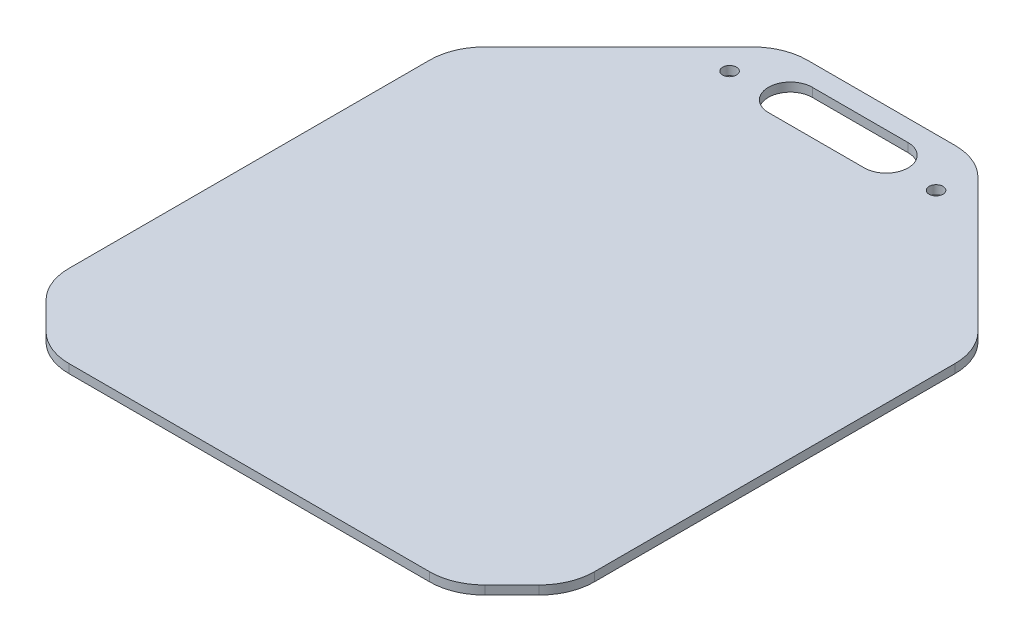
SolidWorks part; units mm, degrees
ref_plane "Front Plane" through (0, 0, 0) normal (0, 0, 1) x (1, 0, 0)
ref_plane "Top Plane" through (0, 0, 0) normal (0, 1, 0) x (1, 0, 0)
ref_plane "Right Plane" through (0, 0, 0) normal (1, 0, 0) x (0, 0, -1)
sketch "Sketch1" plane through (0, 0, 0) normal (0, 1, 0) x (1, 0, 0)
  line L0 (0, 0) -> (294, 0)
  line L1 (294, 0) -> (336.996, 43.004)
  line L2 (336.996, 43.004) -> (336.996, 337.004)
  line L3 (336.996, 337.004) -> (217, 457)
  line L4 (217, 457) -> (77, 457)
  line L5 (77, 457) -> (-42.996, 337.004)
  line L6 (-42.996, 337.004) -> (-42.996, 43.004)
  line L7 (-42.996, 43.004) -> (0, 0)
  dimension "D1" = 294
  dimension "D2" = 294
  dimension "D3" = 457
  dimension "D4" = 43.004
  dimension "D5" = 60.8112
  dimension "D6" = 42.996
  dimension "D7" = 169.7
  dimension "D8" = 119.996
  dimension "D9" = 225
  dimension "D10" = 140
  dimension "D11" = 119.996
extrude "Body" add sketch "Sketch1" along normal blind 6.35
sketch "Sketch2" plane through (0, 6.35, 0) normal (0, 1, 0) x (1, 0, 0)
  line L3 (217, 457) -> (77, 457) construction
  line L4 (112.35, 441.8) -> (181.65, 441.8)
  line L5 (112.35, 441.8) -> (112.35, 410.1)
  line L6 (112.35, 410.1) -> (181.65, 410.1)
  line L7 (181.65, 441.8) -> (181.65, 410.1)
  line L8 (217, 457) -> (77, 457)
  arc A1 (112.35, 441.8) -> (112.35, 410.1) centre (112.35, 425.95) ccw
  arc A2 (181.65, 441.8) -> (181.65, 410.1) centre (181.65, 425.95) cw
  point P8 (147, 410.1)
  point P9 (147, 457)
  dimension "D3" = 15.85
  dimension "D4" = 15.2
  dimension "D1" = 69.3
  dimension "D2" = 31.7
extrude "Handle" cut sketch "Sketch2" against normal blind 6.35 contours L6 A2 L4 A1
sketch "Sketch11" plane through (0, 6.35, 0) normal (0, 1, 0) x (1, 0, 0)
  line L0 (217, 457) -> (77, 457) construction
  circle A0 centre (221.65, 422) radius 5
  arc A1 (181.65, 410.1) -> (181.65, 441.8) centre (181.65, 425.95) ccw construction
  circle A2 centre (72.35, 422) radius 5
  arc A3 (112.35, 441.8) -> (112.35, 410.1) centre (112.35, 425.95) ccw construction
  dimension "D1" = 35
  dimension "D3" = 35
  dimension "D5" = 10
  dimension "D6" = 10
  dimension "D2" = 40
  dimension "D4" = 40
extrude "Locking Mechanism Holes" cut sketch "Sketch11" against normal blind 6.36 contours A0 | A2
fillet "Fillet1" radius 40 2 edges at (217, 3.175, -457) (77, 3.175, -457)
fillet "Fillet2" radius 40 6 edges at (-42.996, 3.175, -337.004) (-42.996, 3.175, -43.004) (0, 3.175, 0) (294, 3.175, 0) (336.996, 3.175, -43.004) (336.996, 3.175, -337.004)
sketch "Sketch12" plane through (0, 0, 0) normal (0, -1, 0) x (1, 0, 0)
  line L0 (112.35, -410.1) -> (181.65, -410.1) construction
  line L6 (299.4, -215.9) -> (-5.4, -215.9)
  line L7 (299.4, -215.9) -> (299.4, -165.1)
  line L8 (299.4, -165.1) -> (-5.4, -165.1)
  line L9 (-5.4, -215.9) -> (-5.4, -165.1)
  line L12 (-42.996, -59.5704) -> (-42.996, -320.4354)
  line L13 (-31.2803, -348.7197) -> (65.2843, -445.2843)
  line L14 (93.5685, -457) -> (200.4315, -457)
  line L15 (228.7157, -445.2843) -> (325.2803, -348.7197)
  line L16 (336.996, -320.4354) -> (336.996, -59.5704)
  line L17 (325.2829, -31.2887) -> (305.7162, -11.7183)
  line L18 (277.4293, 0) -> (16.5707, 0)
  line L19 (-11.7162, -11.7183) -> (-31.2829, -31.2887)
  line L20 (-42.996, -59.5704) -> (-42.996, -320.4354)
  line L21 (-31.2803, -348.7197) -> (65.2843, -445.2843)
  line L22 (93.5685, -457) -> (200.4315, -457)
  line L23 (228.7157, -445.2843) -> (325.2803, -348.7197)
  line L24 (336.996, -320.4354) -> (336.996, -59.5704)
  line L25 (325.2829, -31.2887) -> (305.7162, -11.7183)
  line L26 (277.4293, 0) -> (16.5707, 0)
  line L27 (-11.7162, -11.7183) -> (-31.2829, -31.2887)
  arc A8 (-42.996, -320.4354) -> (-31.2803, -348.7197) centre (-2.996, -320.4354) ccw
  arc A9 (65.2843, -445.2843) -> (93.5685, -457) centre (93.5685, -417) ccw
  arc A10 (200.4315, -457) -> (228.7157, -445.2843) centre (200.4315, -417) ccw
  arc A11 (325.2803, -348.7197) -> (336.996, -320.4354) centre (296.996, -320.4354) ccw
  arc A12 (336.996, -59.5704) -> (325.2829, -31.2887) centre (296.996, -59.5704) ccw
  arc A13 (305.7162, -11.7183) -> (277.4293, 0) centre (277.4293, -40) ccw
  arc A14 (16.5707, 0) -> (-11.7162, -11.7183) centre (16.5707, -40) ccw
  arc A15 (-31.2829, -31.2887) -> (-42.996, -59.5704) centre (-2.996, -59.5704) ccw
  arc A16 (-42.996, -320.4354) -> (-31.2803, -348.7197) centre (-2.996, -320.4354) ccw
  arc A17 (65.2843, -445.2843) -> (93.5685, -457) centre (93.5685, -417) ccw
  arc A18 (200.4315, -457) -> (228.7157, -445.2843) centre (200.4315, -417) ccw
  arc A19 (325.2803, -348.7197) -> (336.996, -320.4354) centre (296.996, -320.4354) ccw
  arc A20 (336.996, -59.5704) -> (325.2829, -31.2887) centre (296.996, -59.5704) ccw
  arc A21 (305.7162, -11.7183) -> (277.4293, 0) centre (277.4293, -40) ccw
  arc A22 (16.5707, 0) -> (-11.7162, -11.7183) centre (16.5707, -40) ccw
  arc A23 (-31.2829, -31.2887) -> (-42.996, -59.5704) centre (-2.996, -59.5704) ccw
  point P0 (147, -410.1)
  point P1 (147, -215.9)
  dimension "D2" = 165.1
  dimension "D5" = 50.8
  dimension "D6" = 304.8
  dimension "D1" = 0
extrude "Boss-Extrude1" add sketch "Sketch12" along normal blind 12.7 contours L6 L9 L8 L7
sketch "Sketch13" plane through (0, -12.7, 0) normal (0, -1, 0) x (1, 0, 0)
  line L1 (261.3, -203.2) -> (32.7, -203.2)
  line L2 (261.3, -203.2) -> (261.3, -177.8) construction
  line L3 (261.3, -177.8) -> (32.7, -177.8)
  line L4 (299.4, -215.9) -> (299.4, -165.1)
  line L5 (299.4, -165.1) -> (-5.4, -165.1)
  line L6 (-5.4, -165.1) -> (-5.4, -215.9)
  line L7 (-5.4, -215.9) -> (299.4, -215.9)
  line L8 (299.4, -215.9) -> (299.4, -165.1) construction
  line L9 (299.4, -165.1) -> (-5.4, -165.1) construction
  line L10 (-5.4, -165.1) -> (-5.4, -215.9) construction
  line L11 (-5.4, -215.9) -> (299.4, -215.9) construction
  line L12 (32.7, -203.2) -> (32.7, -177.8) construction
  arc A0 (261.3, -203.2) -> (261.3, -177.8) centre (261.3, -190.5) ccw
  arc A1 (32.7, -203.2) -> (32.7, -177.8) centre (32.7, -190.5) cw
  point P12 (261.3, -190.5)
  point P14 (32.7, -190.5)
  point P15 (147, -203.2)
  point P16 (147, -215.9)
  point P18 (299.4, -190.5)
  dimension "D2" = 228.6
  dimension "D3" = 25.4
  dimension "D1" = 0
extrude "Cut-Extrude3" cut sketch "Sketch13" against normal up to surface (12.7 mm away) up to face at (147, 0, -190.5)
